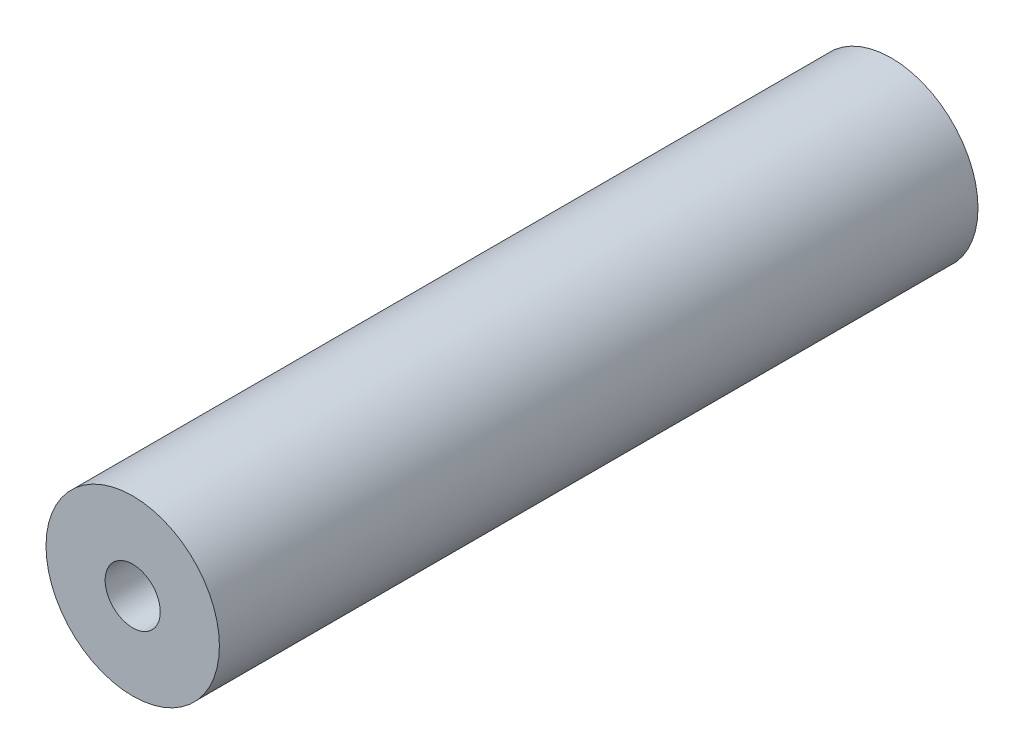
SolidWorks part; units mm, degrees
material "6061-T6 (SS)"
ref_plane "Front Plane" through (0, 0, 0) normal (0, 0, 1) x (1, 0, 0)
ref_plane "Top Plane" through (0, 0, 0) normal (0, 1, 0) x (1, 0, 0)
ref_plane "Right Plane" through (0, 0, 0) normal (1, 0, 0) x (0, 0, -1)
sketch "Sketch1" plane through (0, 0, 0) normal (0, 0, 1) x (1, 0, 0)
  circle A1 centre (0, 0) radius 6.35
  dimension "D2" = 12.7
extrude "Boss-Extrude1" add sketch "Sketch1" along normal mid plane 55.5625
hole_wizard "#10-32 Tapped Hole1" positions "3DSketch1" profile "Sketch2" tap size "#10-32" standard "ANSI Inch"
sketch3d "3DSketch1"
  line L0 (0, 0, 27.7812) -> (0, 0, -27.7812) construction
  point P0 (0, 0, 27.7812)
  point P4 (0, 0, -27.7812)
sketch "Sketch2" plane through (0, 0, 27.7812) normal (1, 0, 0) x (0, -1, 0)
  line L0 (0, 0) -> (0, 13.2428)
  line L1 (0, 13.2428) -> (2.0193, 12.0294)
  line L2 (2.0193, 12.0294) -> (2.0193, 0)
  line L5 (2.0193, 0) -> (0, 0)
  line L10 (0, 13.2428) -> (-2.0193, 12.0294) construction
  line L11 (0, -6.35) -> (0, 107.95) construction
  dimension "Tap Drill Dia." = 4.0386
  dimension "Tap Drill Depth" = 12.0294
  dimension "Drill Angle" = 118
cosmetic thread "Hole Thread1" parameters "D1"=9.652, "D2"=4.826
cosmetic thread "Hole Thread2" parameters "D1"=9.652, "D2"=4.826
